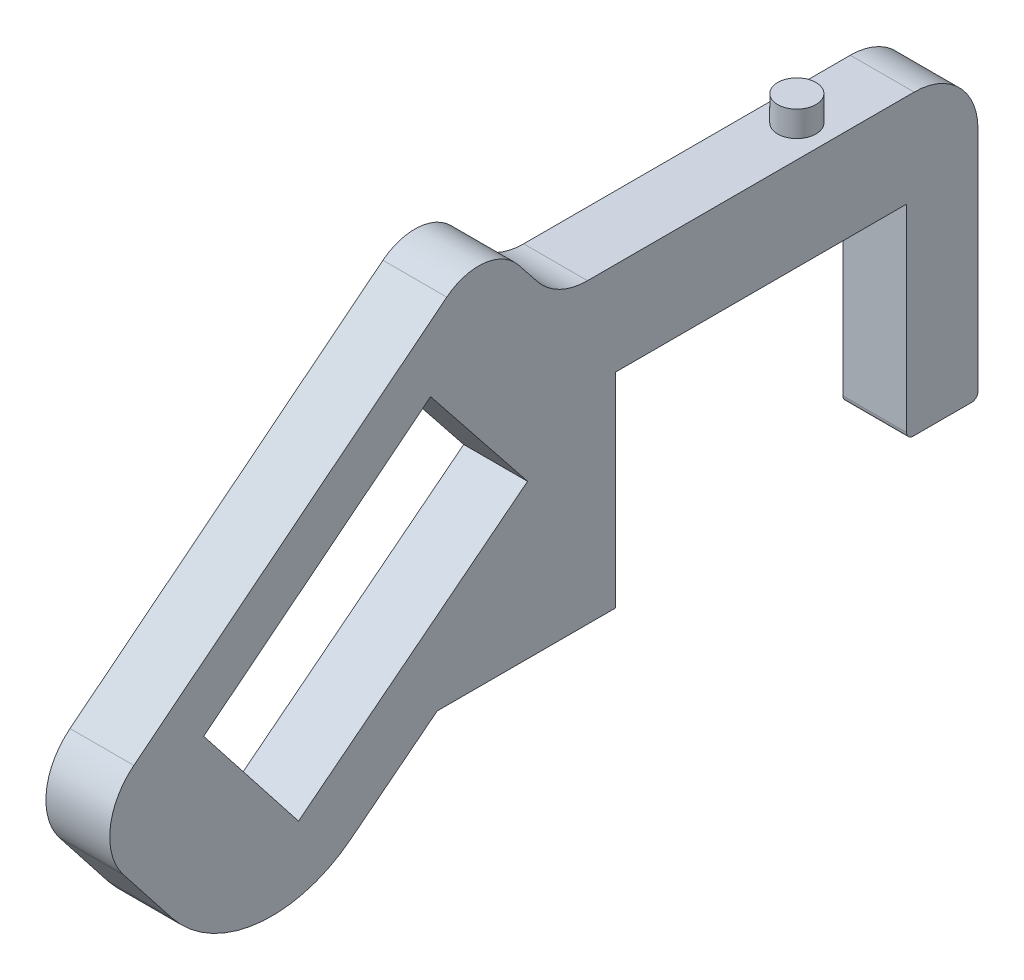
SolidWorks part; units mm, degrees
ref_plane "Plano frontal" through (0, 0, 0) normal (0, 0, 1) x (1, 0, 0)
ref_plane "Plano superior" through (0, 0, 0) normal (0, 1, 0) x (1, 0, 0)
ref_plane "Plano direito" through (0, 0, 0) normal (1, 0, 0) x (0, 0, -1)
sketch "Esboço1" plane through (0, 0, 0) normal (1, 0, 0) x (0, 0, -1)
  line L0 (11.9, -8) -> (16.4859, -8)
  line L1 (-11.4, 8) -> (11.4, 8)
  line L2 (-11.4, 8) -> (-11.4, -8)
  line L3 (-53.0107, -2.9031) -> (-40.6821, -18.6161) construction
  line L4 (11.4, 8) -> (11.4, -7.5)
  line L5 (-11.4, 8) -> (11.4, -8) construction
  line L6 (-11.4, -8) -> (11.4, 8) construction
  line L7 (16.9859, -7.5) -> (16.9859, 10.3)
  line L8 (11.9859, 15.3) -> (-13.5966, 15.3)
  line L9 (-11.4, 8) -> (-11.4, 15.3) construction
  line L10 (-11.4, -8) -> (-11.4, -13) construction
  line L11 (-22.1264, 16.565) -> (-14.5138, 7) construction
  line L12 (-18.3201, 11.7825) -> (-43.6711, -8.3939) construction
  line L13 (-14.5138, 7) -> (-40.0042, -13) construction
  line L14 (-22.1264, 16.565) -> (-47.4116, -3.5591) construction
  line L15 (-47.4116, -3.5591) -> (-40.0042, -13) construction
  line L16 (-40.0042, -13) -> (-11.4, -13) construction
  line L17 (-14.5138, 7) -> (-14.5138, -13) construction
  line L18 (-18.9967, 19.0559) -> (-17.5088, 17.1864)
  line L19 (-25.3728, -8) -> (-11.4, -8)
  line L20 (-49.9456, -6.8095) -> (-46.1771, -11.6126)
  line L21 (-24.6174, 19.6947) -> (-49.1255, 0.1891)
  line L22 (-21.4876, 22.1856) -> (-53.0107, -2.9031) construction
  line L23 (-21.4876, 22.1856) -> (-8.8758, 6.3394) construction
  line L24 (-8.8758, 6.3394) -> (-40.6821, -18.6161) construction
  line L27 (-32.1368, -13.3072) -> (-25.3728, -8)
  line L28 (-30.9956, 1.6943) -> (-27.259, -3) construction
  line L29 (-27.259, -3) -> (-18.2902, 4.037)
  line L30 (-18.2902, 4.037) -> (-25.8821, 13.5759)
  line L31 (-25.8821, 13.5759) -> (-43.6559, -0.5699)
  line L32 (-43.6559, -0.5699) -> (-36.2279, -10.037)
  line L33 (-36.2279, -10.037) -> (-27.259, -3)
  circle A0 centre (-40.0042, -13) radius 34.55 construction
  circle A1 centre (-40.0042, -13) radius 32.4 construction
  arc A2 (-32.1368, -13.3072) -> (-46.1771, -11.6126) centre (-38.3097, -5.4398) cw
  arc A3 (16.9859, 10.3) -> (11.9859, 15.3) centre (11.9859, 10.3) ccw
  arc A5 (-49.9456, -6.8095) -> (-49.1255, 0.1891) centre (-46.0119, -3.7231) cw
  arc A6 (-17.5088, 17.1864) -> (-13.5966, 15.3) centre (-13.5966, 20.3) ccw
  arc A7 (16.4859, -8) -> (16.9859, -7.5) centre (16.4859, -7.5) ccw
  arc A8 (11.9, -8) -> (11.4, -7.5) centre (11.9, -7.5) cw
  arc A9 (-24.6174, 19.6947) -> (-18.9967, 19.0559) centre (-22.1264, 16.565) cw
  point P0 (0, 0)
  point P29 (16.9859, 15.3)
  point P40 (16.9859, -8)
  dimension "D4" = 69.1
  dimension "D5" = 64.8
  dimension "D9" = 16
  dimension "D10" = 0.5
  dimension "D11" = 4
  dimension "D12" = 10
  dimension "D1" = 16
  dimension "D2" = 22.8
  dimension "D3" = 23.3
  dimension "D6" = 32.4
  dimension "D7" = 12
  dimension "D8" = 4
extrude "Ressalto-extrusão2" add sketch "Esboço1" along normal blind 5
sketch "Esboço2" plane through (0, 15.3, 0) normal (0, 1, 0) x (1, 0, 0)
  line L0 (2.5, 16.9859) -> (2.5, 5.2959) construction
  line L1 (5, 16.9859) -> (0, 16.9859) construction
  circle A0 centre (2.5, 5.2959) radius 1.5
  dimension "D1" = 11.69
  dimension "D2" = 3
extrude "Ressalto-extrusão3" add sketch "Esboço2" along normal blind 2
